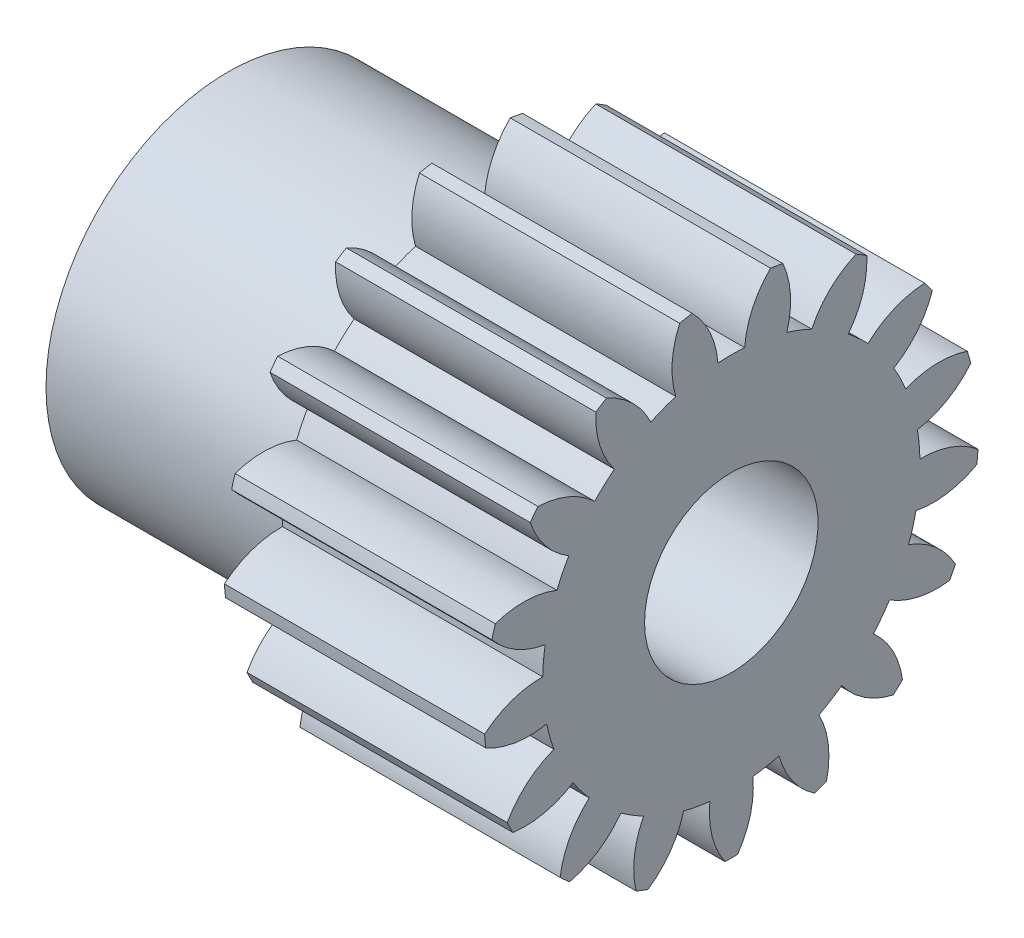
SolidWorks part; units mm, degrees
ref_plane "Plane1" through (0, 0, 0) normal (0, 0, 1) x (1, 0, 0)
ref_plane "Plane2" through (0, 0, 0) normal (0, 1, 0) x (1, 0, 0)
ref_plane "Plane3" through (0, 0, 0) normal (1, 0, 0) x (0, 0, -1)
other "Configuration Table"
sketch "HoldingSke" plane through (0, 0, 0) normal (0, 1, 0) x (1, 0, 0)
  line L0 (0, 0) -> (0.6375, -0.1949)
  line L1 (-15, 0) -> (100, 0) construction
  line L2 (0, 0) -> (-2.1039, 2.3779)
  line L3 (0, 0) -> (-11.863, 4.5341)
  line L4 (0, 0) -> (8.2586, 2.5249)
  line L5 (0, 0) -> (-27.1716, -10.1342)
  line L6 (0, 0) -> (-12.4344, -8.3896)
  line L7 (-2.1039, 2.3779) -> (4.1384, 30.6981)
  line L8 (-76.2, 54.61) -> (-74.4, 54.61)
  line L9 (-71.009, 38.7566) -> (-53.1078, 45.2721)
  line L10 (-76.2, 71.12) -> (104.1128, 71.12)
  line L11 (0, 0) -> (-15, 0)
  line L12 (-76.2, 101.6) -> (-76.147, 101.6)
  line L13 (24.9733, 27.94) -> (52.9518, 28.4284)
  line L14 (24.9733, 27.94) -> (24.9743, 27.94)
  line L15 (24.9733, 27.94) -> (100.4006, 29.5858)
  line L16 (-63.627, -1.5) -> (-12.827, -1.5)
  circle A0 centre (0, 0) radius 5
  circle A1 centre (0, 0) radius 10.5
  circle A2 centre (0, 0) radius 10.5
  circle A3 centre (0, 0) radius 5
  dimension "MHD" = 21
  dimension "Hub_dia" = 21
  dimension "Bore" = 10
  dimension "MBD" = 10
  dimension "Num_teeth" = 17
  dimension "Pitch" = 0.6667
  dimension "Overall_len" = 29
  dimension "Show_teeth" = 17
  dimension "Thickness" = 15
  dimension "OAL" = 29.0001
  dimension "T_dim" = 1.8
  dimension "Ap" = 20
  dimension "H" = 19.05
  dimension "Pitch_radius" = 180.3128
  dimension "Width" = 15
  dimension "Backlash" = 0.053
  dimension "Addendum_fac" = 1
  dimension "Dedendum_fac" = 1.25
  dimension "Clearance_fac" = 0.25
  dimension "Dedendum_add" = 0.001
  dimension "Module" = 1.5
sketch "BasProSke" plane through (0, 0, 0) normal (0, 1, 0) x (1, 0, 0)
  line L0 (-10, 0) -> (60, 0) construction
  line L1 (0, 0) -> (0, 14.25)
  line L2 (0, 0) -> (15, 0)
  line L3 (15, 0) -> (15, 14.25)
  line L4 (15, 14.25) -> (0, 14.25)
  dimension "Thickness" = 15
  dimension "Diameter" = 28.5
revolve "Base-Revolve" add sketch "BasProSke" angle 360 about L0
sketch "TooCutSke" plane through (0, 0, 0) normal (1, 0, 0) x (0, 0, -1)
  line L1 (0, 0) -> (0, 107) construction
  line L2 (0, 0) -> (-1.2691, 12.6867) construction
  line L3 (0, 0) -> (-4.6687, 24.9751) construction
  line L4 (-1.2691, 12.6867) -> (-2.3343, 12.4876) construction
  arc A0 (0.7694, 10.8467) -> (-0.7694, 10.8467) centre (0, 0) ccw
  arc A1 (2.2806, 14.0921) -> (-2.2806, 14.0921) centre (0, 0) ccw
  circle A2 centre (0, 0) radius 12.75 construction
  circle A3 centre (0, 0) radius 11.9811 construction
  arc A4 (-0.7694, 10.8467) -> (-2.2806, 14.0921) centre (-5.8542, 10.4535) ccw
  arc A5 (2.2806, 14.0921) -> (0.7694, 10.8467) centre (5.8542, 10.4535) ccw
  dimension "Root_dia" = 21.748
  dimension "Overcut_dia" = 28.5508
  dimension "Pitch_dia" = 25.5
  dimension "Base_dia" = 23.9622
  dimension "Flank_rad" = 5.1
  dimension "Half_ang" = 10.588
  dimension "Half_CT" = 1.0837
extrude "ToothCut" cut sketch "TooCutSke" along normal through all
fillet "Breaks" [suppressed] radius 0.03
fillet "RootFillets" [suppressed] radius 0.376
pattern_circular "TeethCuts" count 17 every 21.176 about axis through (-10, 0, 0) along (1, 0, 0) of "ToothCut", "RootFillets", "Breaks"
sketch "HubNeaOneSke" plane through (0, 0, 0) normal (-1, 0, 0) x (0, 0, 1)
  circle A0 centre (0, 0) radius 10.5
  dimension "Diameter" = 21
extrude "HubNearOne" add sketch "HubNeaOneSke" along normal blind 14.0001
sketch "HubNeaBotSke" plane through (0, 0, 0) normal (-1, 0, 0) x (0, 0, 1)
  circle A0 centre (0, 0) radius 10.5
  dimension "Diameter" = 21
extrude "HubNearBoth" [suppressed] add sketch "HubNeaBotSke" along normal blind 7
ref_plane "FarPln" through (15, 0, 0) normal (1, 0, 0) x (0, 0, -1)
sketch "HubFarSke" plane through (15, 0, 0) normal (1, 0, 0) x (0, 0, -1)
  circle A0 centre (0, 0) radius 10.5
  dimension "Diameter" = 21
extrude "HubFar" [suppressed] add sketch "HubFarSke" along normal blind 7
sketch "BorSke" plane through (0, 0, 0) normal (1, 0, 0) x (0, 0, -1)
  circle A0 centre (0, 0) radius 5
  dimension "Diameter" = 10
extrude "Bore" cut sketch "BorSke" along normal mid plane 58.0001
sketch "KeySke" plane through (0, 0, 0) normal (1, 0, 0) x (0, 0, -1)
  line L0 (-2, 0) -> (-2, 6.8)
  line L1 (-2, 6.8) -> (2, 6.8)
  line L2 (2, 6.8) -> (2, 0)
  line L3 (0, 0) -> (0, 34) construction
  line L4 (-2, 0) -> (2, 0)
  dimension "Offset" = 6.8
  dimension "Width" = 4
extrude "Keyway" [suppressed] cut sketch "KeySke" along normal mid plane 58.0001
pattern_circular "Keyway2" [suppressed] count 2 every 90 about axis through (-10, 0, 0) along (1, 0, 0)
equation "' \"Module@HoldingSke\" = 6.35"
equation "' \"Num_teeth@HoldingSke\" = 12"
equation "' \"Ap@HoldingSke\" =  20"
equation "' \"Ap@HoldingSke\" = 20"
equation "' \"Width@HoldingSke\" = 0.5 * 25.4"
equation "' \"Hub_dia@HoldingSke\"= 1 * 25.4"
equation "' \"Hub_dia@HoldingSke\" = 1 * 25.4"
equation "' \"Overall_len@HoldingSke\" = 1.0 * 25.4"
equation "' \"Bore@HoldingSke\" = 0.75 * 25.4"
equation "' \"T_dim@HoldingSke\" = 0.1 * 25.4"
equation "' \"Width@KeySke\" = 0.25 * 25.4"
equation "' \"Show_teeth@HoldingSke\" = 13"
equation "' \"Backlash@HoldingSke\" = 0.009 * 25.4"
equation "' \"Addendum_fac@HoldingSke\" = 1.0"
equation "' \"Dedendum_fac@HoldingSke\" = 1.25"
equation "' \"Dedendum_add@HoldingSke\" = 0.00005 * 25.4"
equation "' \"Clearance_fac@HoldingSke\" = 0.25"
equation "\"Pitch@HoldingSke\" = 1 / \"Module@HoldingSke\""
equation "\"Overcut_dia@TooCutSke\" = (\"Num_teeth@HoldingSke\" + 2 * \"Addendum_fac@HoldingSke\") / \"Pitch@HoldingSke\" + 0.002 * 25.4"
equation "\"Pitch_dia@TooCutSke\" = \"Num_teeth@HoldingSke\" / \"Pitch@HoldingSke\""
equation "\"Base_dia@TooCutSke\" = \"Num_teeth@HoldingSke\" / \"Pitch@HoldingSke\" * cos((\"Ap@HoldingSke\"  * 3.14159265 / 180))"
equation "\"Root_dia@TooCutSke\" = (\"Num_teeth@HoldingSke\" + 2) / \"Pitch@HoldingSke\" - 2 * (\"Addendum_fac@HoldingSke\" + \"Dedendum_fac@HoldingSke\") / \"Pitch@HoldingSke\" - \"Dedendum_add@HoldingSke\" * 2"
equation "\"Half_ang@TooCutSke\" = 180 / \"Num_teeth@HoldingSke\""
equation "\"Half_CT@TooCutSke\" = \"Num_teeth@HoldingSke\" / \"Pitch@HoldingSke\" * sin((3.14159265 / 2 / \"Num_teeth@HoldingSke\")) / 2 - 7 * \"Backlash@HoldingSke\" / 4"
equation "\"Flank_rad@TooCutSke\" = \"Num_teeth@HoldingSke\" / \"Pitch@HoldingSke\" / 5"
equation "\"Radius@RootFillets\" = \"Clearance_fac@HoldingSke\" / \"Pitch@HoldingSke\" + \"Dedendum_add@HoldingSke\""
equation "\"Break_rad@Breaks\" = 0.02 / \"Pitch@HoldingSke\""
equation "\"Thickness@HoldingSke\" = \"Width@HoldingSke\""
equation "\"OAL@HoldingSke\" = \"Thickness@HoldingSke\""
equation "\"MHD@HoldingSke\" = (\"Num_teeth@HoldingSke\" + 2) / \"Pitch@HoldingSke\" - 2 * (\"Addendum_fac@HoldingSke\" + \"Dedendum_fac@HoldingSke\")  / \"Pitch@HoldingSke\" - \"Dedendum_add@HoldingSke\" * 2"
equation "\"MBD@HoldingSke\" = (\"Num_teeth@HoldingSke\" + 2) / \"Pitch@HoldingSke\" - 2 * (\"Addendum_fac@HoldingSke\" + \"Dedendum_fac@HoldingSke\")  / \"Pitch@HoldingSke\" - \"Dedendum_add@HoldingSke\" * 2 - 0.002 * 25.4"
equation "\"MHD@HoldingSke\" = ((sgn( \"MHD@HoldingSke\" - \"Hub_dia@HoldingSke\" )-1)*( \"MHD@HoldingSke\" - \"Hub_dia@HoldingSke\" ))/-2+ \"Hub_dia@HoldingSke\""
equation "\"MBD@HoldingSke\" = ((sgn( \"MBD@HoldingSke\" - \"Bore@HoldingSke\" )-1)*( \"MBD@HoldingSke\" - \"Bore@HoldingSke\" ))/-2+ \"Bore@HoldingSke\""
equation "\"OAL@HoldingSke\" = ((sgn( \"OAL@HoldingSke\" - \"Overall_len@HoldingSke\" )+1)*( \"OAL@HoldingSke\" - \"Overall_len@HoldingSke\" ))/2 + \"Overall_len@HoldingSke\" + 0.000002 * 25.4"
equation "\"Num_teeth@TeethCuts\" = int( \"Show_teeth@HoldingSke\" ) + 1"
equation "\"Num_teeth@TeethCuts\" = ((sgn( \"Num_teeth@TeethCuts\" - \"Num_teeth@HoldingSke\" )-1)*( \"Num_teeth@TeethCuts\" - \"Num_teeth@HoldingSke\" ))/-2+ \"Num_teeth@HoldingSke\""
equation "\"Num_teeth@TeethCuts\" = ((sgn( \"Num_teeth@TeethCuts\" - 2.0)+1)*( \"Num_teeth@TeethCuts\" - 2.0))/2 +2.0"
equation "\"Angle@TeethCuts\" = 360.0 / \"Num_teeth@HoldingSke\""
equation "\"Diameter@BasProSke\" = (\"Num_teeth@HoldingSke\" + 2 * \"Addendum_fac@HoldingSke\") / \"Pitch@HoldingSke\""
equation "\"Thickness@BasProSke\"  = \"Thickness@HoldingSke\""
equation "' \"Fillet_rad@BasProSke\" =  \"Thickness@HoldingSke\" * 0.05"
equation "' \"Fillet_rad@BasProSke\" = \"Thickness@HoldingSke\" * 0.05"
equation "\"MHD@HoldingSke\" = ((sgn( \"MHD@HoldingSke\" - \"Root_dia@TooCutSke\" )-1)*( \"MHD@HoldingSke\" - \"Root_dia@TooCutSke\" ))/-2+ \"Root_dia@TooCutSke\""
equation "\"Diameter@HubNeaOneSke\" = \"MHD@HoldingSke\""
equation "\"Length@HubNearOne\" = \"OAL@HoldingSke\" - \"Thickness@BasProSke\""
equation "\"Diameter@HubNeaBotSke\" = \"MHD@HoldingSke\""
equation "\"Length@HubNearBoth\" = ( \"OAL@HoldingSke\" - \"Thickness@BasProSke\" ) / 2.0"
equation "\"Thickness@FarPln\" = \"Thickness@BasProSke\""
equation "\"Diameter@HubFarSke\" = \"MHD@HoldingSke\""
equation "\"Length@HubFar\" = ( \"OAL@HoldingSke\" - \"Thickness@BasProSke\" ) / 2.0"
equation "\"Diameter@BorSke\" = \"MBD@HoldingSke\""
equation "\"D1@Bore\" = \"OAL@HoldingSke\" * 2.0"
equation "\"D1@Keyway\" = \"OAL@HoldingSke\" * 2.0"
equation "\"Offset@KeySke\" = \"T_dim@HoldingSke\" + \"MBD@HoldingSke\" / 2.0"
